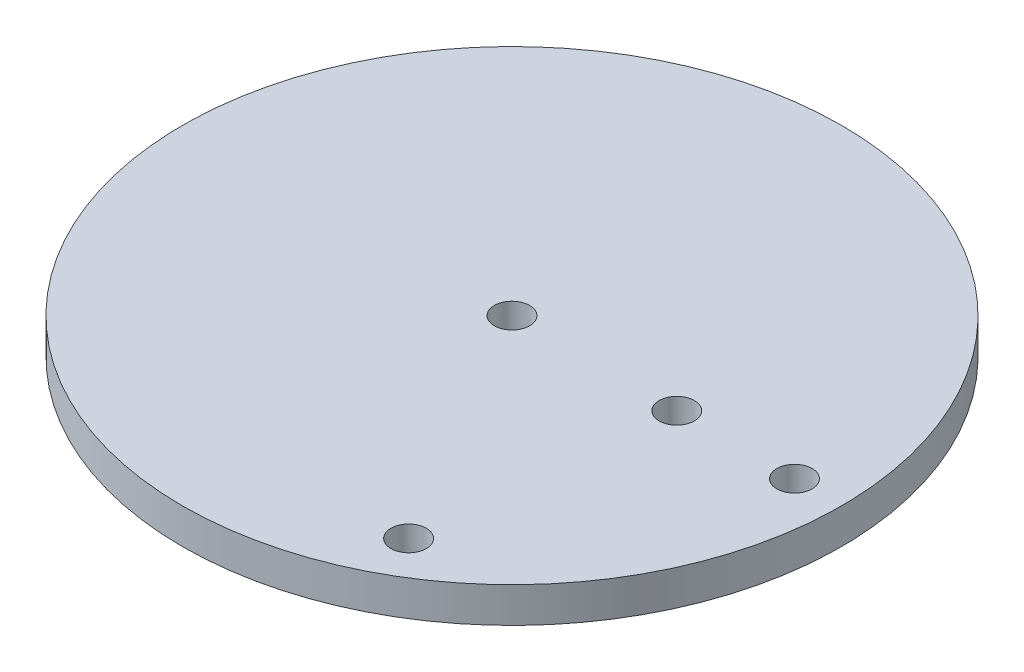
SolidWorks part; units mm, degrees
ref_plane "Front Plane" through (0, 0, 0) normal (0, 0, 1) x (1, 0, 0)
ref_plane "Top Plane" through (0, 0, 0) normal (0, 1, 0) x (1, 0, 0)
ref_plane "Right Plane" through (0, 0, 0) normal (1, 0, 0) x (0, 0, -1)
sketch "Sketch1" plane through (0, 0, 0) normal (0, 1, 0) x (1, 0, 0)
  line L0 (0, 0) -> (24, 0) construction
  line L1 (0, 0) -> (12, -20.7846) construction
  circle A0 centre (0, 0) radius 28
  circle A1 centre (0, 0) radius 1.5
  circle A2 centre (24, 0) radius 1.5
  circle A5 centre (14, 0) radius 1.5
  circle A6 centre (12, -20.7846) radius 1.5
  dimension "D1" = 56
  dimension "D2" = 3
  dimension "D3" = 14
  dimension "D5" = 24
  dimension "D4" = 24
  dimension "D6" = 60
extrude "Boss-Extrude1" add sketch "Sketch1" along normal mid plane 3
